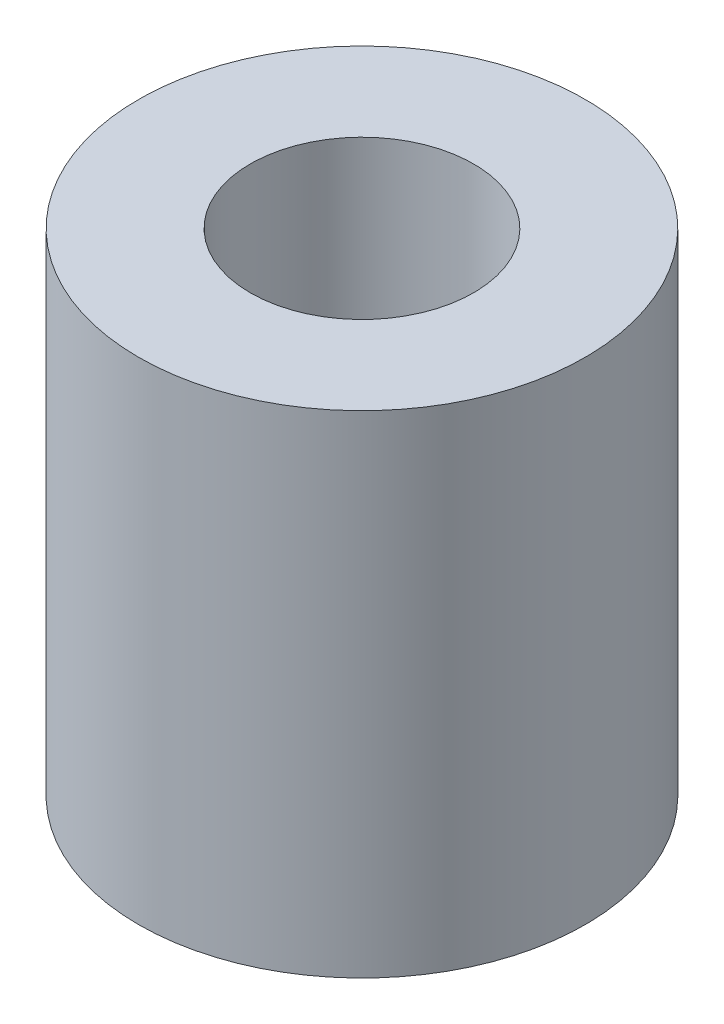
SolidWorks part; units mm, degrees
ref_plane "Front Plane" through (0, 0, 0) normal (0, 0, 1) x (1, 0, 0)
ref_plane "Top Plane" through (0, 0, 0) normal (0, 1, 0) x (1, 0, 0)
ref_plane "Right Plane" through (0, 0, 0) normal (1, 0, 0) x (0, 0, -1)
sketch "Sketch1" plane through (0, 0, 0) normal (0, 1, 0) x (1, 0, 0)
  circle A0 centre (0, 0) radius 2.5
  circle A1 centre (0, 0) radius 5
  dimension "D1" = 10
  dimension "D2" = 5
extrude "Boss-Extrude1" add sketch "Sketch1" along normal blind 11
